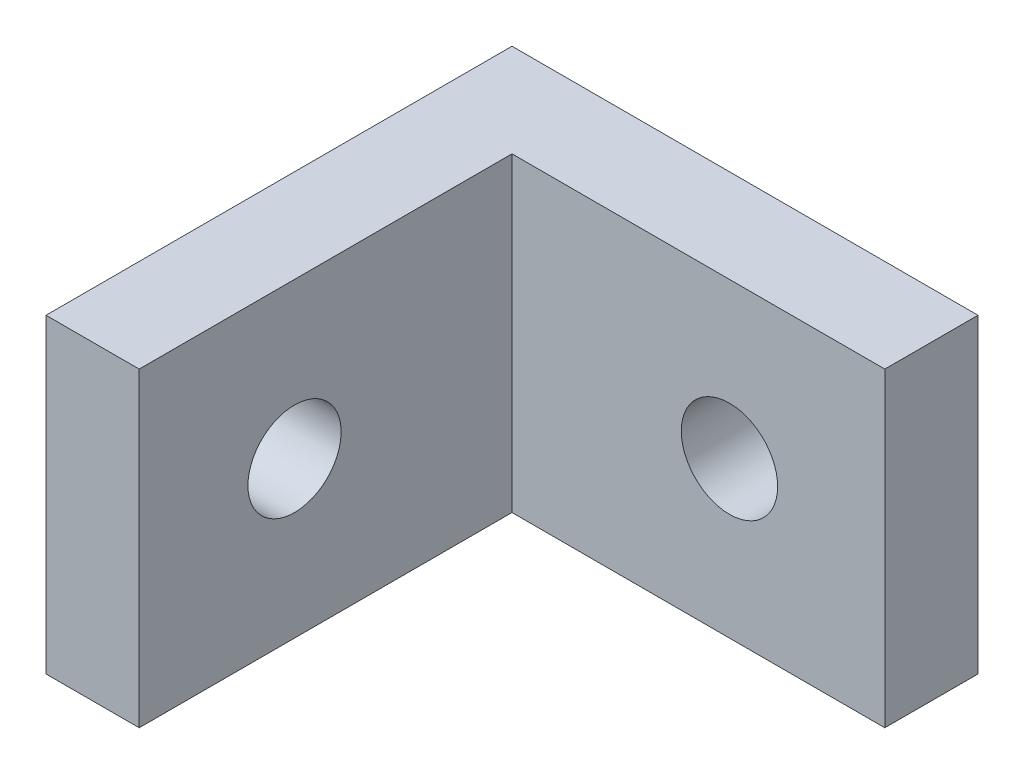
SolidWorks part; units mm, degrees
ref_plane "前视基准面" through (0, 0, 0) normal (0, 0, 1) x (1, 0, 0)
ref_plane "上视基准面" through (0, 0, 0) normal (0, 1, 0) x (1, 0, 0)
ref_plane "右视基准面" through (0, 0, 0) normal (1, 0, 0) x (0, 0, -1)
sketch "草图1" plane through (0, 0, 0) normal (0, 0, 1) x (1, 0, 0)
  line L1 (7.5, -5) -> (-7.5, -5)
  line L2 (7.5, -5) -> (7.5, 5)
  line L3 (7.5, 5) -> (-7.5, 5)
  line L4 (-7.5, -5) -> (-7.5, 5)
  line L5 (7.5, -5) -> (-7.5, 5) construction
  line L6 (7.5, 5) -> (-7.5, -5) construction
  point P0 (0, 0)
  dimension "D1" = 15
  dimension "D2" = 10
extrude "凸台-拉伸1" add sketch "草图1" along normal blind 3
sketch "草图2" plane through (0, 0, 3) normal (0, 0, 1) x (1, 0, 0)
  line L0 (-7.5, -5) -> (7.5, -5) construction
  line L1 (-7.5, 5) -> (-4.5, 5)
  line L2 (-7.5, 5) -> (-7.5, -5)
  line L3 (-7.5, -5) -> (-4.5, -5)
  line L4 (-4.5, 5) -> (-4.5, -5)
  dimension "D1" = 3
extrude "凸台-拉伸2" add sketch "草图2" along normal blind 12
sketch "草图3" plane through (0, 0, 0) normal (0, 0, -1) x (-1, 0, 0)
  line L0 (7.5, 0) -> (-2.5, 0) construction
  line L1 (7.5, 5) -> (7.5, -5) construction
  circle A0 centre (-2.5, 0) radius 1.55
  dimension "D1" = 3.1
  dimension "D2" = 10
extrude "切除-拉伸1" cut sketch "草图3" against normal through all contours A0
sketch "草图4" plane through (-7.5, 0, 0) normal (-1, 0, 0) x (0, 0, 1)
  line L0 (0, 0) -> (10, 0) construction
  circle A0 centre (10, 0) radius 1.5
  dimension "D1" = 3
  dimension "D2" = 10
extrude "切除-拉伸2" cut sketch "草图4" against normal through all
